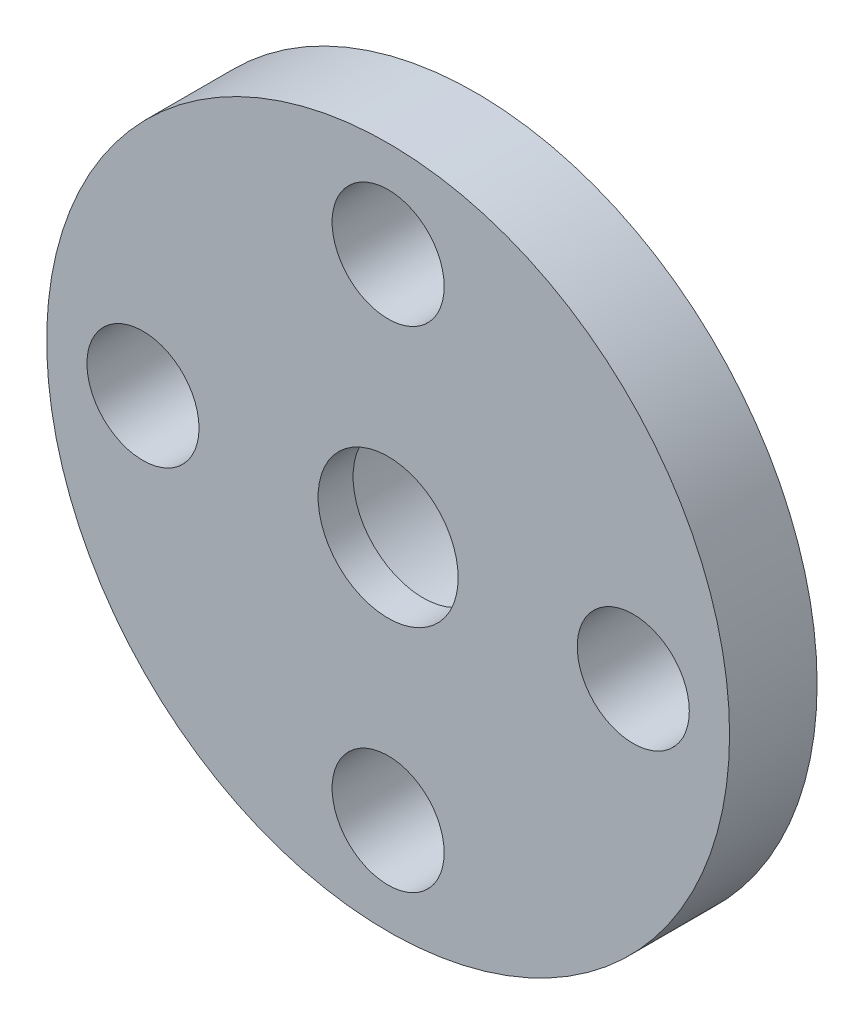
SolidWorks part; units mm, degrees
ref_plane "Ön Düzlem" through (0, 0, 0) normal (0, 0, 1) x (1, 0, 0)
ref_plane "Üst Düzlem" through (0, 0, 0) normal (0, 1, 0) x (1, 0, 0)
ref_plane "Sağ Düzlem" through (0, 0, 0) normal (1, 0, 0) x (0, 0, -1)
sketch "Çizim1" plane through (0, 0, 0) normal (0, 0, 1) x (1, 0, 0)
  line L0 (-7, 0) -> (0, 0) construction
  line L1 (0, 0) -> (0, 7) construction
  line L2 (0, -7) -> (0, 0) construction
  line L3 (0, 0) -> (7, 0) construction
  circle A0 centre (0, 0) radius 9.75
  circle A1 centre (0, 0) radius 4
  circle A3 centre (-7, 0) radius 1.6
  circle A4 centre (0, 7) radius 1.6
  circle A5 centre (7, 0) radius 1.6
  circle A6 centre (0, -7) radius 1.6
  dimension "D1" = 19.5
  dimension "D2" = 8
  dimension "D3" = 7
  dimension "D4" = 3.2
extrude "Yükseklik-Ekstrüzyon4" add sketch "Çizim1" along normal blind 2.5 contours A3 | A0 | A4 | A5 | A6
sketch "Çizim13" plane through (0, 0, 0) normal (0, 0, -1) x (-1, 0, 0)
  circle A0 centre (0, 0) radius 4
  dimension "D1" = 8
extrude "Yükseklik-Ekstrüzyon6" add sketch "Çizim13" along normal blind 3
sketch "Çizim14" plane through (0, 0, -3) normal (0, 0, -1) x (-1, 0, 0)
  circle A0 centre (0, 0) radius 3
  dimension "D1" = 6
extrude "Kes-Ekstrüzyon4" cut sketch "Çizim14" against normal offset from surface (4.5 mm away) 1 up to face at (8.6, 0, 2.5)
sketch "Çizim15" plane through (0, 0, 2.5) normal (0, 0, 1) x (1, 0, 0)
  circle A0 centre (0, 0) radius 2
  dimension "D1" = 4
extrude "Kes-Ekstrüzyon5" cut sketch "Çizim15" against normal blind 2.5
